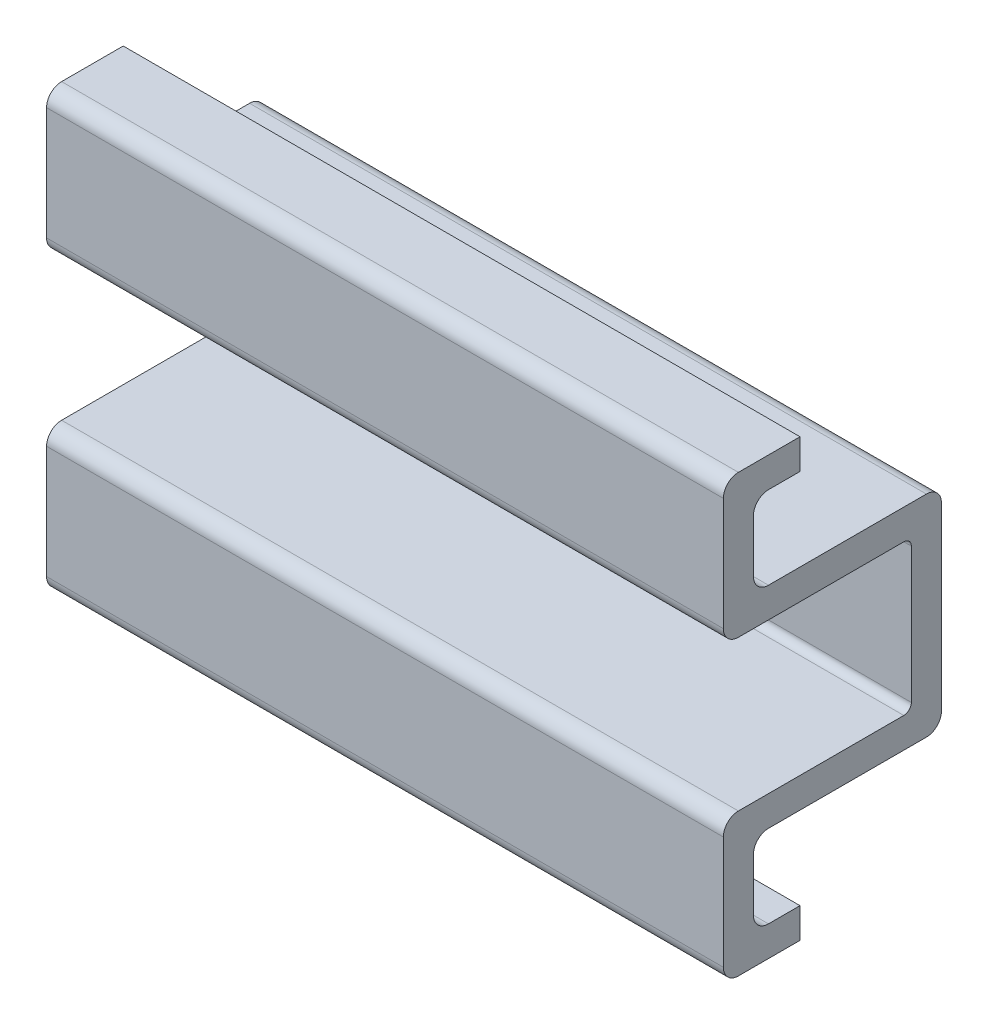
SolidWorks part; units mm, degrees
ref_plane "Front Plane" through (0, 0, 0) normal (0, 0, 1) x (1, 0, 0)
ref_plane "Top Plane" through (0, 0, 0) normal (0, 1, 0) x (1, 0, 0)
ref_plane "Right Plane" through (0, 0, 0) normal (1, 0, 0) x (0, 0, -1)
sketch "Sketch1" plane through (0, 0, 0) normal (0, 1, 0) x (1, 0, 0)
  line L0 (0, -63.3372) -> (0, 83.1005) construction
sketch "Sketch3" plane through (0, 0, 0) normal (1, 0, 0) x (0, 0, -1)
  line L0 (-5.7293, 5) -> (-5.7293, -5)
  line L1 (-63.3372, 0) -> (83.1005, 0) construction
  line L2 (-5.7293, -5) -> (-18.2293, -5)
  line L3 (-5.7293, 0) -> (-3.7293, 0)
  line L4 (-3.7293, 7) -> (-3.7293, -7)
  line L5 (-3.7293, -7) -> (-16.2293, -7)
  line L6 (-16.2293, -7) -> (-16.2293, -12.5)
  line L7 (-16.2293, -12.5) -> (-14.5224, -12.5)
  line L8 (-18.2293, -5) -> (-18.2293, -14.5)
  line L9 (-18.2293, -14.5) -> (-13.1317, -14.5)
  line L10 (-13.1317, -14.5) -> (-13.1317, -12.5)
  line L11 (-13.1317, -12.5) -> (-14.5224, -12.5)
  line L12 (-14.5224, 0) -> (7.8467, 0)
  line L13 (-13.1317, 14.5) -> (-13.1317, 12.5)
  line L14 (-18.2293, 14.5) -> (-13.1317, 14.5)
  line L15 (-18.2293, 5) -> (-18.2293, 14.5)
  line L16 (-5.7293, 5) -> (-18.2293, 5)
  line L17 (-3.7293, 7) -> (-16.2293, 7)
  line L18 (-16.2293, 7) -> (-16.2293, 12.5)
  line L19 (-16.2293, 12.5) -> (-14.5224, 12.5)
  line L20 (-13.1317, 12.5) -> (-14.5224, 12.5)
  dimension "D1" = 12.5
  dimension "D2" = 5
  dimension "D3" = 2
  dimension "D4" = 2
  dimension "D5" = 12.5
  dimension "D6" = 1.7068
  dimension "D7" = 5.5
  dimension "D8" = 9.5
extrude "Boss-Extrude1" add sketch "Sketch3" along normal blind 45 contours L10 L11 L7 L6 L5 L4 L3 L0 L2 L8 L9 | L20 L13 L14 L15 L16 L0 L3 L4 L17 L18 L19
fillet "Fillet1" radius 1 10 edges at (22.5, 5, 18.2293) (22.5, -5, 18.2293) (22.5, -14.5, 18.2293) (22.5, 14.5, 18.2293) (22.5, 12.5, 16.2293) (22.5, -12.5, 16.2293) (22.5, -7, 16.2293) (22.5, 7, 16.2293) (22.5, 7, 3.7293) (22.5, -7, 3.7293)
fillet "Fillet2" radius 0.5 2 edges at (22.5, 5, 5.7293) (22.5, -5, 5.7293)
